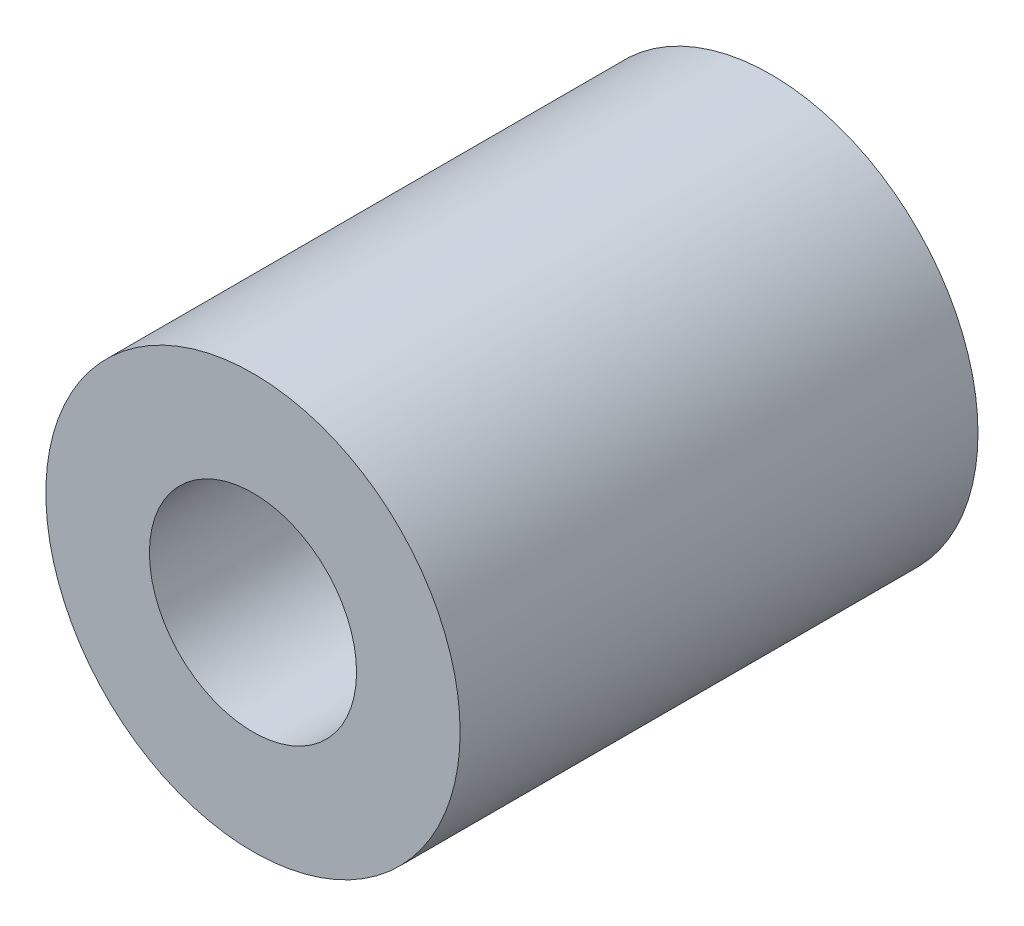
SolidWorks part; units mm, degrees
ref_plane "前视基准面" through (0, 0, 0) normal (0, 0, 1) x (1, 0, 0)
ref_plane "上视基准面" through (0, 0, 0) normal (0, 1, 0) x (1, 0, 0)
ref_plane "右视基准面" through (0, 0, 0) normal (1, 0, 0) x (0, 0, -1)
sketch "草图1" plane through (0, 0, 0) normal (0, 0, 1) x (1, 0, 0)
  line L0 (-66.2613, 0) -> (0, 0) construction
  line L1 (0, 0) -> (0, 74.9438) construction
  circle A0 centre (0, 0) radius 1
  circle A1 centre (0, 0) radius 2
  dimension "D1" = 2
  dimension "D2" = 4
extrude "凸台-拉伸1" add sketch "草图1" along normal blind 5
